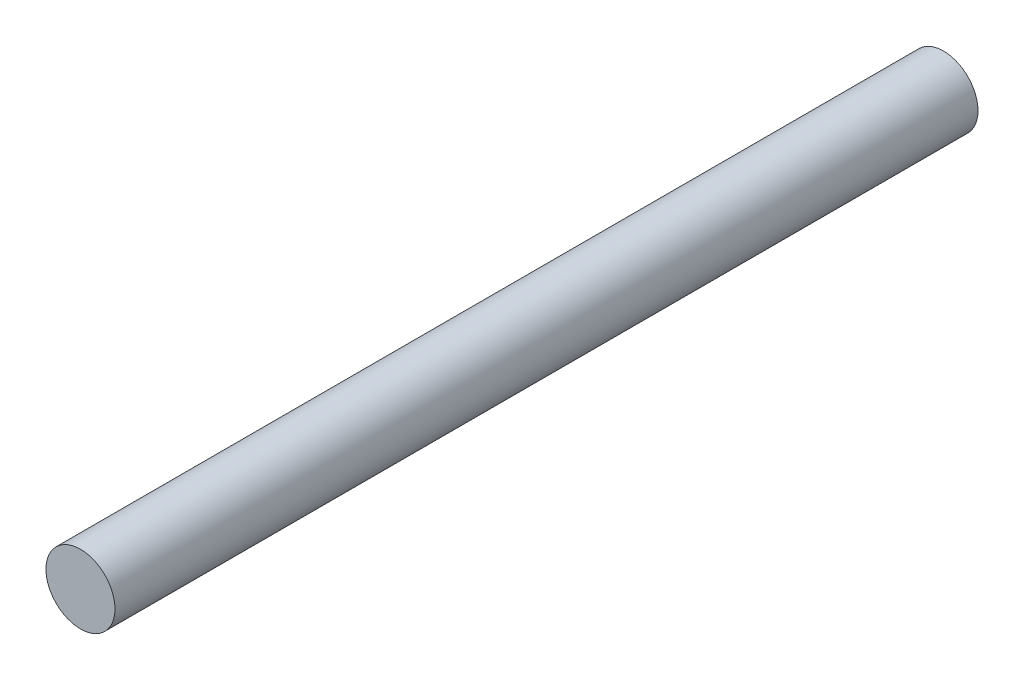
SolidWorks part; units mm, degrees
ref_plane "前视基准面" through (0, 0, 0) normal (0, 0, 1) x (1, 0, 0)
ref_plane "上视基准面" through (0, 0, 0) normal (0, 1, 0) x (1, 0, 0)
ref_plane "右视基准面" through (0, 0, 0) normal (1, 0, 0) x (0, 0, -1)
sketch "草图1" plane through (0, 0, 0) normal (0, 0, 1) x (1, 0, 0)
  circle A0 centre (0, 0) radius 4
extrude "凸台-拉伸1" add sketch "草图1" along normal blind 100
